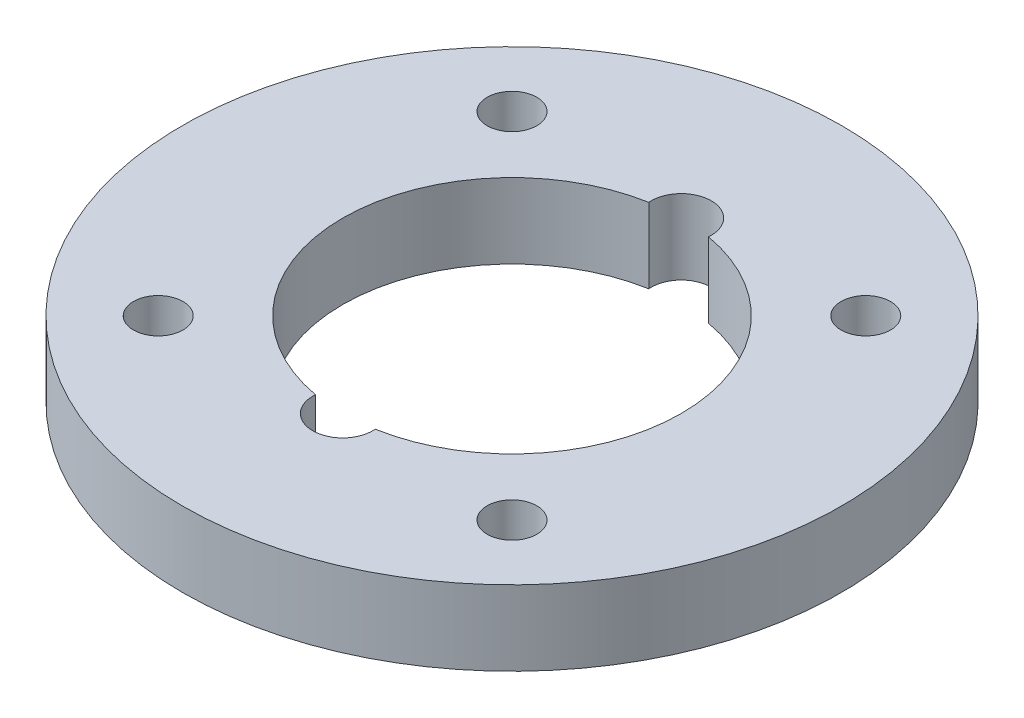
SolidWorks part; units mm, degrees
ref_plane "Front Plane" through (0, 0, 0) normal (0, 0, 1) x (1, 0, 0)
ref_plane "Top Plane" through (0, 0, 0) normal (0, 1, 0) x (1, 0, 0)
ref_plane "Right Plane" through (0, 0, 0) normal (1, 0, 0) x (0, 0, -1)
sketch "0.5in Socket" plane through (0, 0, 0) normal (0, 1, 0) x (1, 0, 0)
  line L0 (0, 0) -> (-14.997, 14.997) construction
  line L1 (14.997, -14.997) -> (0, 0) construction
  line L2 (-14.997, -14.997) -> (0, 0) construction
  line L3 (0, 0) -> (14.997, 14.997) construction
  line L4 (0, 0) -> (0, -14.351) construction
  circle A0 centre (0, 0) radius 27.94
  circle A1 centre (0, 0) radius 2.5527
  arc A2 (-2.53, 14.1262) -> (2.53, 14.1262) centre (0, 14.351) cw
  arc A3 (2.53, 14.1262) -> (2.53, -14.1262) centre (0, 0) cw
  arc A4 (2.53, -14.1262) -> (-2.53, -14.1262) centre (0, -14.351) cw
  arc A5 (-2.53, -14.1262) -> (-2.53, 14.1262) centre (0, 0) cw
  circle A6 centre (14.997, -14.997) radius 2.1
  circle A7 centre (14.997, 14.997) radius 2.1
  circle A8 centre (-14.997, 14.997) radius 2.1
  circle A9 centre (-14.997, -14.997) radius 2.1
  point P4 (0, 0)
  point P8 (0, -14.351)
  point P9 (0, 0)
  point P10 (0, 14.351)
  point P16 (0, 0)
  dimension "D1" = 55.88
  dimension "D2" = 5.1054
  dimension "D4" = 14.351
  dimension "D5" = 14.351
  dimension "D7" = 2.54
  dimension "D8" = 2.54
  dimension "D9" = 4.2
  dimension "D10" = 4.2
  dimension "D11" = 4.2
  dimension "D12" = 4.2
  dimension "D13" = 21.209
  dimension "D17" = 90
  dimension "D3" = 28.702
  dimension "D6" = 14.351
  dimension "D14" = 21.209
  dimension "D15" = 21.209
  dimension "D16" = 21.209
  dimension "D18" = 90
  dimension "D19" = 90
  dimension "D20" = 45
extrude "Boss-Extrude1" add sketch "0.5in Socket" along normal blind 6.35 contours A0 A9 A8 A7 A6 A4 A5 A2 A3
